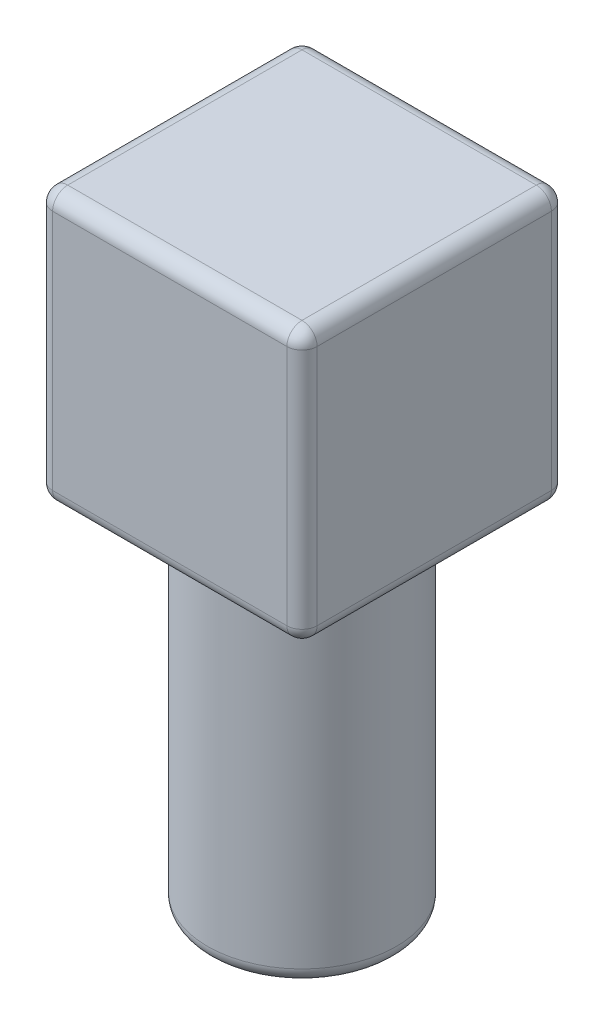
SolidWorks part; units mm, degrees
ref_plane "Front Plane" through (0, 0, 0) normal (0, 0, 1) x (1, 0, 0)
ref_plane "Top Plane" through (0, 0, 0) normal (0, 1, 0) x (1, 0, 0)
ref_plane "Right Plane" through (0, 0, 0) normal (1, 0, 0) x (0, 0, -1)
sketch "Sketch1" plane through (0, 0, 0) normal (0, 1, 0) x (1, 0, 0)
  circle A0 centre (0, 0) radius 12.5
extrude "Boss-Extrude1" add sketch "Sketch1" along normal blind 47 contours A0
sketch "Sketch2" plane through (0, 47, 0) normal (0, 1, 0) x (1, 0, 0)
  line L5 (-17.5, -17.5) -> (17.5, -17.5)
  line L6 (-17.5, -17.5) -> (-17.5, 17.5)
  line L7 (-17.5, 17.5) -> (17.5, 17.5)
  line L8 (17.5, -17.5) -> (17.5, 17.5)
  line L9 (-17.5, -17.5) -> (17.5, 17.5) construction
  line L10 (-17.5, 17.5) -> (17.5, -17.5) construction
  point P0 (0, 0)
extrude "Boss-Extrude2" add sketch "Sketch2" along normal blind 36 contours L7 L8 L5 L6
fillet "Fillet1" radius 2 13 edges at (-17.5, 47, 0) (0, 47, -17.5) (17.5, 47, 0) (0, 47, 17.5) (-17.5, 83, 0) (0, 83, -17.5) (17.5, 83, 0) (0, 83, 17.5) (-17.5, 65, -17.5) (17.5, 65, -17.5) (17.5, 65, 17.5) (-17.5, 65, 17.5) (0, 0, 12.5)
